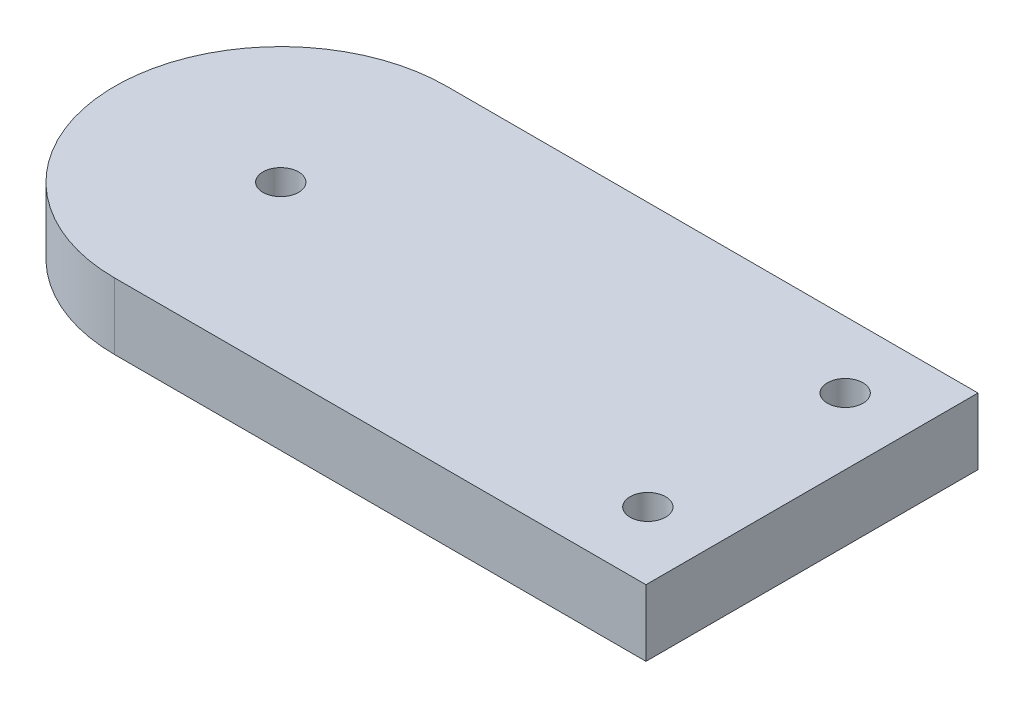
SolidWorks part; units mm, degrees
ref_plane "Front Plane" through (0, 0, 0) normal (0, 0, 1) x (1, 0, 0)
ref_plane "Top Plane" through (0, 0, 0) normal (0, 1, 0) x (1, 0, 0)
ref_plane "Right Plane" through (0, 0, 0) normal (1, 0, 0) x (0, 0, -1)
sketch "Sketch2" plane through (0, 0, 0) normal (0, 1, 0) x (1, 0, 0)
  line L0 (0, 0) -> (0, 15.875)
  line L5 (-25.4, 0) -> (0, 0)
  line L6 (-25.4, 15.875) -> (0, 15.875)
  arc A1 (-25.4, 0) -> (-25.4, 15.875) centre (-25.4, 7.9375) cw
  circle A2 centre (-25.4, 7.9375) radius 0.8509
  circle A3 centre (-3.175, 12.7) radius 0.8509
  circle A4 centre (-3.175, 3.2639) radius 0.8509
  point P3 (0, 7.9375)
  point P7 (-3.175, 3.2639)
  point P9 (-3.175, 12.7)
  point P15 (-3.175, 11.9266)
  dimension "D2" = 7.9375
  dimension "D4" = 1.7018
  dimension "D1" = 25.4
  dimension "D3" = 3.175
  dimension "D5" = 3.175
  dimension "D6" = 3.2639
extrude "Boss-Extrude1" add sketch "Sketch2" along normal blind 3.175
